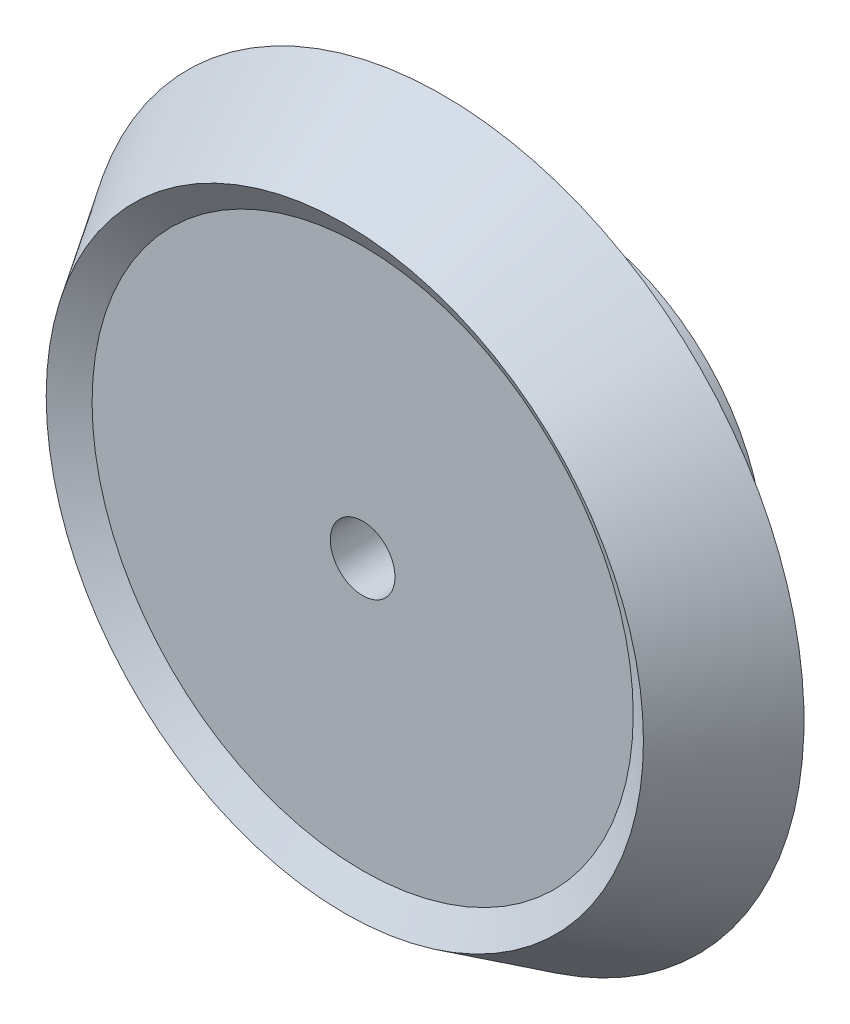
SolidWorks part; units mm, degrees
ref_plane "Ön Düzlem" through (0, 0, 0) normal (0, 0, 1) x (1, 0, 0)
ref_plane "Üst Düzlem" through (0, 0, 0) normal (0, 1, 0) x (1, 0, 0)
ref_plane "Sağ Düzlem" through (0, 0, 0) normal (1, 0, 0) x (0, 0, -1)
sketch "Çizim1" plane through (0, 0, 0) normal (1, 0, 0) x (0, 0, -1)
  line L0 (100.2447, 0) -> (-83.9941, 0) construction
  line L1 (0, 7.25) -> (0, 60.707)
  line L2 (0, 60.707) -> (-4, 67)
  line L3 (-4, 67) -> (18.0257, 81)
  line L4 (18.0257, 81) -> (26, 68.4543)
  line L5 (0, 7.25) -> (46, 7.25)
  line L6 (46, 7.25) -> (46, 44)
  line L8 (26, 68.4543) -> (26, 54)
  line L9 (36, 44) -> (46, 44)
  arc A2 (26, 54) -> (36, 44) centre (36, 54) ccw
  dimension "D4" = 10
  dimension "D8" = 67
  dimension "D1" = 4
  dimension "D2" = 14.5
  dimension "D3" = 44
  dimension "D5" = 50
  dimension "D6" = 30
  dimension "D7" = 81
revolve "Döndür1" add sketch "Çizim1" angle 360 about L0
